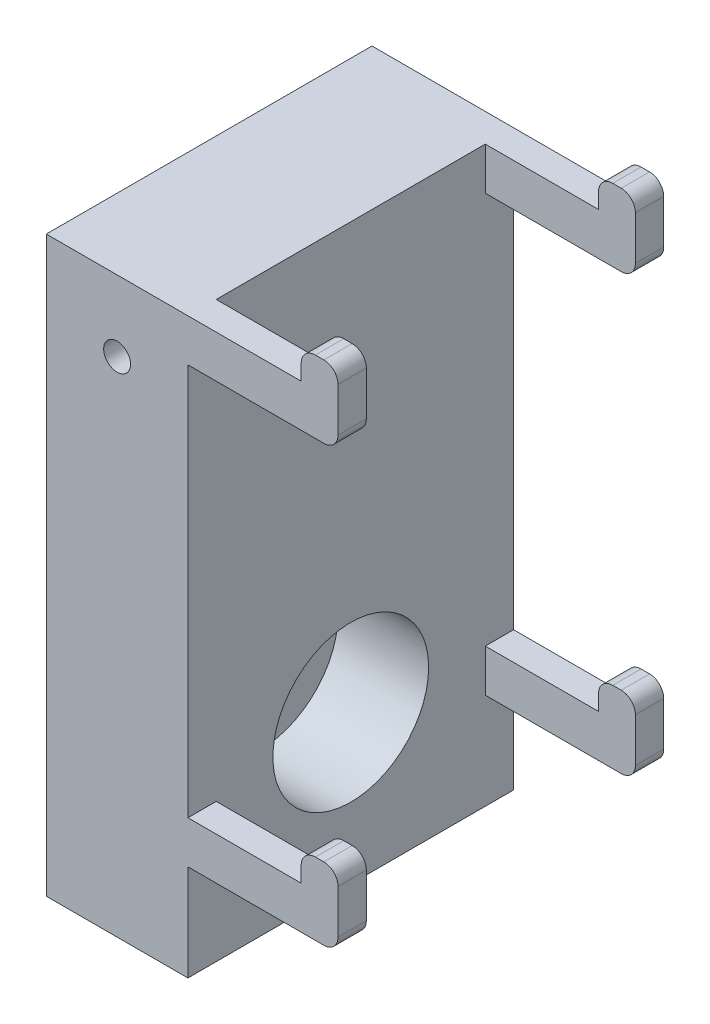
SolidWorks part; units mm, degrees
ref_plane "Front Plane" through (0, 0, 0) normal (0, 0, 1) x (1, 0, 0)
ref_plane "Top Plane" through (0, 0, 0) normal (0, 1, 0) x (1, 0, 0)
ref_plane "Right Plane" through (0, 0, 0) normal (1, 0, 0) x (0, 0, -1)
sketch "Sketch1" plane through (0, 0, 0) normal (1, 0, 0) x (0, 0, -1)
  line L0 (-22.1162, 0) -> (22.1162, 0) construction
  line L7 (-11.5, 0) -> (11.5, 0)
  line L8 (-11.5, 0) -> (-11.5, -40.5)
  line L9 (-11.5, -40.5) -> (11.5, -40.5)
  line L10 (11.5, 0) -> (11.5, -40.5)
  point P2 (0, 0)
  dimension "D1" = 0
  dimension "D2" = 23
  dimension "D4" = 40.5
extrude "Boss-Extrude1" add sketch "Sketch1" along normal blind 10
sketch "Esquisse3" plane through (10, 0, 0) normal (1, 0, 0) x (0, 0, -1)
  point P0 (0, -30)
  dimension "D1" = 30
hole_wizard "Chambrage pour vis à six pans creux M61" positions "Esquisse3" profile "Esquisse2" counterbore size "M6" standard "ISO" end condition up to next
sketch "Esquisse2" plane through (10, -30, 0) normal (0, 1, 0) x (0, 0, -1)
  line L0 (0, 0) -> (0, 10)
  line L1 (0, 10) -> (3.3, 10)
  line L3 (3.3, 10) -> (3.3, 6.4)
  line L4 (3.3, 6.4) -> (5.5, 6.4)
  line L5 (5.5, 6.4) -> (5.5, 0)
  line L7 (5.5, 0) -> (0, 0)
  line L11 (0, -6.35) -> (0, 107.95) construction
  dimension "Diamètre du perçage jusqu'au prochain" = 6.6
  dimension "Profondeur du perçage jusqu'au prochain" = 10
  dimension "Diamètre du chambrage" = 11
  dimension "Profondeur du chambrage" = 6.4
sketch "Sketch2" plane through (10, 0, 0) normal (1, 0, 0) x (0, 0, -1)
  circle A0 centre (0, -20) radius 3.5
  dimension "D2" = 7
  dimension "D1" = 20
extrude "Cut-Extrude1" [suppressed] cut sketch "Sketch2" against normal blind 10
sketch "Sketch3" [suppressed] plane through (10, 0, 0) normal (1, 0, 0) x (0, 0, -1)
  circle A0 centre (0, -20) radius 5.5
  dimension "D1" = 11
extrude "Cut-Extrude2" [suppressed] cut sketch "Sketch3" against normal blind 7
sketch "Sketch4" plane through (0, 0, 11.5) normal (0, 0, 1) x (1, 0, 0)
  line L0 (10, 0) -> (18, 0)
  line L2 (10, -3) -> (19.6, -3)
  line L3 (20.6, -2) -> (20.6, 1.1)
  line L4 (19.6, 2.1) -> (19, 2.1)
  line L5 (18, 1.1) -> (18, 0)
  line L11 (10, 0) -> (10, -3)
  line L13 (10, 0) -> (10, -40.5) construction
  line L14 (10, -23.5) -> (10, -16.5) construction
  line L16 (10, -30.7) -> (18, -30.7)
  line L17 (10, -33.7) -> (19.6, -33.7)
  line L18 (20.6, -32.7) -> (20.6, -29.6)
  line L19 (19.6, -28.6) -> (19, -28.6)
  line L20 (18, -29.6) -> (18, -30.7)
  line L21 (10, -30.7) -> (10, -33.7)
  line L22 (10, 0) -> (10, -30.7) construction
  arc A1 (19.6, -3) -> (20.6, -2) centre (19.6, -2) ccw
  arc A4 (20.6, 1.1) -> (19.6, 2.1) centre (19.6, 1.1) ccw
  arc A5 (19, 2.1) -> (18, 1.1) centre (19, 1.1) ccw
  arc A6 (19.6, -33.7) -> (20.6, -32.7) centre (19.6, -32.7) ccw
  arc A7 (20.6, -29.6) -> (19.6, -28.6) centre (19.6, -29.6) ccw
  arc A8 (19, -28.6) -> (18, -29.6) centre (19, -29.6) ccw
  point P28 (18, 2.1)
  dimension "D3" = 1
  dimension "D1" = 3
  dimension "D2" = 2.6
  dimension "D4" = 2
  dimension "D5" = 8
  dimension "D6" = 30.7
  dimension "D8" = 2.1
extrude "Boss-Extrude2" add sketch "Sketch4" against normal blind 2
mirror "Mirror1" about plane through (0, 0, 0) normal (0, 0, 1) of "Boss-Extrude2"
ref_plane "Plane1" through (0, 0, 6) normal (0, 0, 1) x (1, 0, 0)
ref_plane "Plane2" through (0, 0, -6) normal (0, 0, 1) x (1, 0, 0)
sketch "Sketch8" plane through (0, 0, -6) normal (0, 0, 1) x (1, 0, 0)
  line L0 (9, 5) -> (9, 12.8202) construction
  line L6 (9, 1.9966) -> (9, 0)
  line L7 (18, 0) -> (0, 0) construction
  line L8 (9, 0) -> (11.1161, 0)
  arc A1 (11.1161, 0) -> (9, 1.9966) centre (9.1161, 0) ccw
  dimension "D1" = 2
  dimension "D2" = 1.9966
revolve "Revolve1" [suppressed] add sketch "Sketch8" angle 360 about L0
mirror "Mirror2" [suppressed] about plane through (0, 0, 0) normal (0, 0, 1)
sketch "Sketch9" plane through (0, 0, 0) normal (0, 1, 0) x (1, 0, 0)
  line L0 (5.9672, 0.0466) -> (5.9672, 0.726)
  line L1 (5.9672, 0.726) -> (7.6021, 0.2453)
  line L2 (7.6021, 0.2453) -> (7.6021, -0.2445)
  line L3 (7.6021, -0.2445) -> (5.9672, -0.7252)
  line L4 (5.9672, -0.7252) -> (5.9672, 0.0466)
  line L5 (5.4672, 1.3942) -> (5.4672, -1.3934)
  line L6 (5.4672, -1.3934) -> (7.6436, -0.7534)
  line L7 (5.4672, 1.3942) -> (7.6436, 0.7542)
  line L8 (7.4642, 1.0757) -> (7.7663, 1.338)
  line L9 (7.5555, -0.9494) -> (7.8981, -1.1559)
  arc A0 (7.9907, 0.0004) -> (7.7663, 1.338) centre (6.7847, 0.4857) ccw
  arc A1 (7.9907, 0.0004) -> (7.8981, -1.1559) centre (6.7847, -0.4848) cw
  arc A2 (7.4642, 1.0757) -> (7.6436, 0.7542) centre (6.7847, 0.4857) cw
  arc A3 (7.6436, -0.7534) -> (7.5446, -0.9669) centre (6.7847, -0.4848) cw
  dimension "D4" = 1.3
  dimension "D5" = 1.3
  dimension "D6" = 0.9
  dimension "D7" = 0.9
  dimension "D1" = 0.5
  dimension "D2" = 0.5
  dimension "D3" = 0.5
extrude "Cut-Extrude4" [suppressed] cut sketch "Sketch9" against normal blind 1 contours L6 A3 L9 A1 A0 L8 A2 L7 L5 L3 L4 L0 L1 L2
ref_plane "Plane18" through (0, 0, 11.5) normal (1, 0, 0) x (0, 0, -1)
sketch "Esquisse5" plane through (0, 0, 11.5) normal (0, 0, 1) x (1, 0, 0)
  circle A0 centre (5, -5) radius 0.95
  dimension "D1" = 1.9
extrude "Enlèv. mat.-Extru.1" cut sketch "Esquisse5" against normal blind 4
mirror "Symétrie1" about plane through (0, 0, 0) normal (0, 0, 1) of "Enlèv. mat.-Extru.1"
